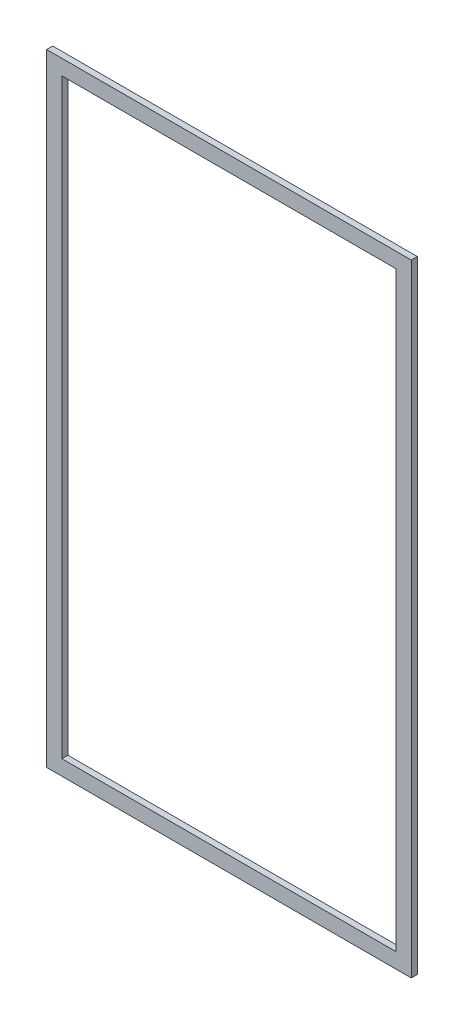
SolidWorks part; units mm, degrees
ref_plane "Front Plane" through (0, 0, 0) normal (0, 0, 1) x (1, 0, 0)
ref_plane "Top Plane" through (0, 0, 0) normal (0, 1, 0) x (1, 0, 0)
ref_plane "Right Plane" through (0, 0, 0) normal (1, 0, 0) x (0, 0, -1)
sketch "Sketch3" plane through (0, 0, 0) normal (0, 0, 1) x (1, 0, 0)
  line L1 (300, -511.5) -> (-300, -511.5)
  line L2 (300, -511.5) -> (300, 511.5)
  line L3 (300, 511.5) -> (-300, 511.5)
  line L4 (-300, -511.5) -> (-300, 511.5)
  line L5 (300, -511.5) -> (-300, 511.5) construction
  line L6 (300, 511.5) -> (-300, -511.5) construction
  line L7 (275, -486.5) -> (-275, -486.5)
  line L8 (275, -486.5) -> (275, 486.5)
  line L9 (275, 486.5) -> (-275, 486.5)
  line L10 (-275, -486.5) -> (-275, 486.5)
  line L11 (275, -486.5) -> (-275, 486.5) construction
  line L12 (275, 486.5) -> (-275, -486.5) construction
  point P0 (0, 0)
  point P6 (0, 0)
extrude "Boss-Extrude2" add sketch "Sketch3" along normal blind 10
